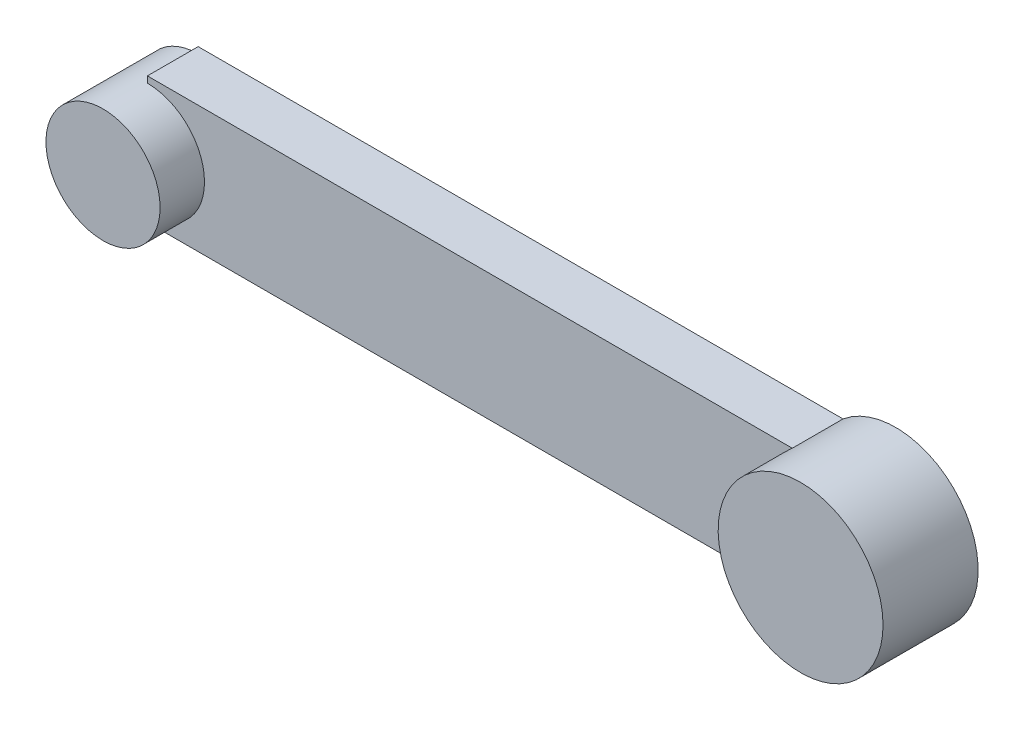
SolidWorks part; units mm, degrees
ref_plane "前视基准面" through (0, 0, 0) normal (0, 0, 1) x (1, 0, 0)
ref_plane "上视基准面" through (0, 0, 0) normal (0, 1, 0) x (1, 0, 0)
ref_plane "右视基准面" through (0, 0, 0) normal (1, 0, 0) x (0, 0, -1)
other "Configuration Table"
sketch "草图1" plane through (0, 0, 0) normal (0, 0, 1) x (1, 0, 0)
  line L1 (0, 105000) -> (110000, 105000)
  line L2 (0, 105000) -> (0, 125000)
  line L3 (0, 125000) -> (110000, 125000)
  line L4 (110000, 105000) -> (110000, 125000)
extrude "凸台-拉伸1" add sketch "草图1" along normal blind 8000
sketch "草图2" plane through (0, 0, 0) normal (0, 0, 1) x (1, 0, 0)
  line L0 (0, 125000) -> (0, 105000) construction
  circle A0 centre (0, 115000) radius 9000
extrude "凸台-拉伸2" add sketch "草图2" along normal blind 15000
sketch "草图3" plane through (0, 0, 0) normal (0, 0, 1) x (1, 0, 0)
  line L0 (110000, 105000) -> (110000, 125000) construction
  circle A0 centre (110000, 115000) radius 13000
extrude "凸台-拉伸3" add sketch "草图3" along normal blind 15000
